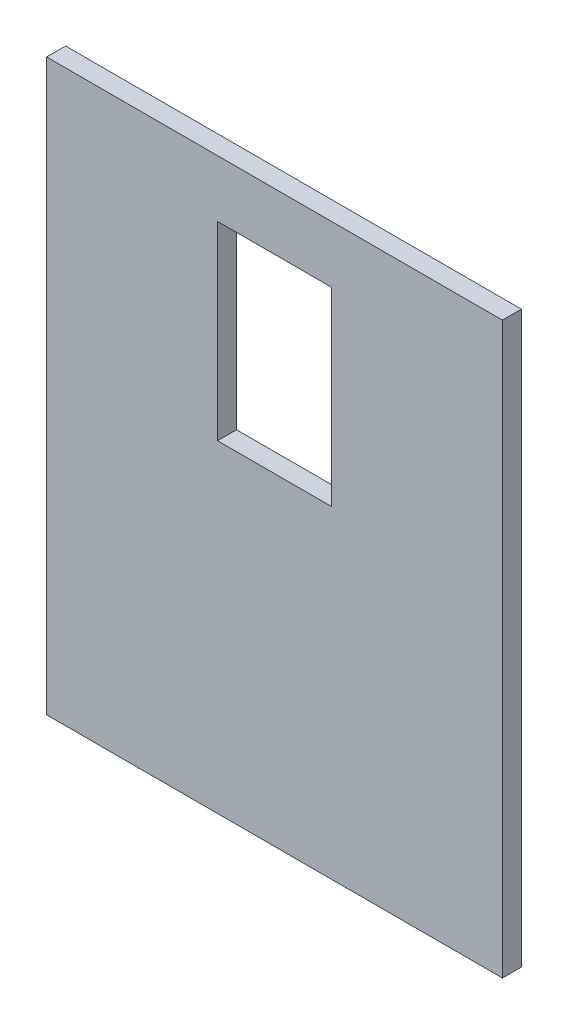
SolidWorks part; units mm, degrees
ref_plane "Front Plane" through (0, 0, 0) normal (0, 0, 1) x (1, 0, 0)
ref_plane "Top Plane" through (0, 0, 0) normal (0, 1, 0) x (1, 0, 0)
ref_plane "Right Plane" through (0, 0, 0) normal (1, 0, 0) x (0, 0, -1)
sketch "Sketch1" plane through (0, 0, 0) normal (0, 0, 1) x (1, 0, 0)
  line L0 (0, 75) -> (0, -75) construction
  line L5 (-60, -75) -> (60, -75)
  line L6 (-60, -75) -> (-60, 75)
  line L7 (-60, 75) -> (60, 75)
  line L8 (60, -75) -> (60, 75)
  line L9 (-60, -75) -> (60, 75) construction
  line L10 (-60, 75) -> (60, -75) construction
  line L12 (-15, 10) -> (15, 10)
  line L13 (-15, 10) -> (-15, 60)
  line L14 (-15, 60) -> (15, 60)
  line L15 (15, 10) -> (15, 60)
  line L16 (-15, 10) -> (15, 60) construction
  line L17 (-15, 60) -> (15, 10) construction
  point P0 (0, 0)
  point P8 (0, 35)
  dimension "D1" = 120
  dimension "D2" = 150
  dimension "D3" = 30
  dimension "D4" = 50
  dimension "D5" = 15
extrude "Boss-Extrude1" add sketch "Sketch1" against normal blind 5
